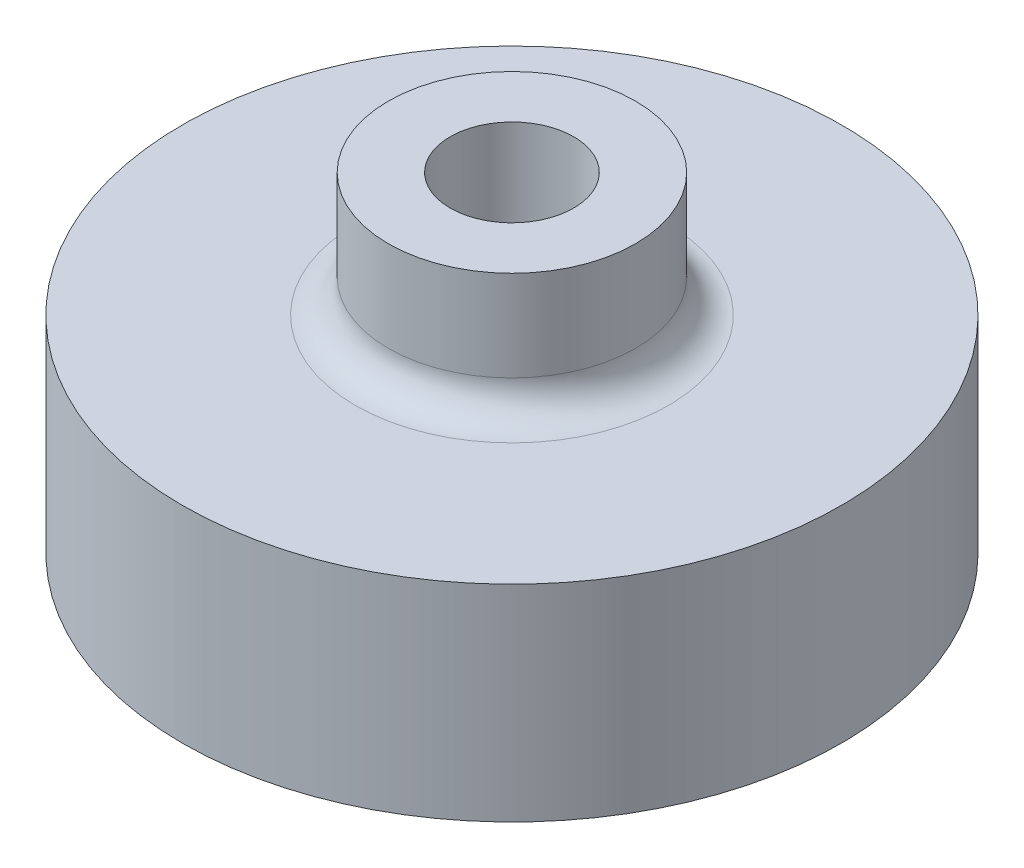
SolidWorks part; units mm, degrees
ref_plane "Front Plane" through (0, 0, 0) normal (0, 0, 1) x (1, 0, 0)
ref_plane "Top Plane" through (0, 0, 0) normal (0, 1, 0) x (1, 0, 0)
ref_plane "Right Plane" through (0, 0, 0) normal (1, 0, 0) x (0, 0, -1)
sketch "Sketch1" plane through (0, 0, 0) normal (0, 1, 0) x (1, 0, 0)
  circle A0 centre (0, 0) radius 1000
extrude "Boss-Extrude1" add sketch "Sketch1" along normal blind 625
sketch "Sketch2" plane through (0, 625, 0) normal (0, 1, 0) x (1, 0, 0)
  circle A0 centre (0, 0) radius 375
extrude "Boss-Extrude2" add sketch "Sketch2" along normal blind 375
fillet "Fillet1" radius 100 1 edges at (0, 625, 375)
sketch "Sketch3" plane through (0, 1000, 0) normal (0, 1, 0) x (1, 0, 0)
  circle A0 centre (0, 0) radius 187.5
extrude "Cut-Extrude1" cut sketch "Sketch3" against normal blind 875
sketch "Sketch4" plane through (0, 0, 0) normal (0, -1, 0) x (-1, 0, 0)
  line L2 (-48.0876, -187.5) -> (-48.0876, 181.2287)
  line L3 (50, -187.5) -> (50, 180.7104)
  arc A0 (50, -180.7104) -> (50, 180.7104) centre (0, 0) ccw
  arc A1 (-48.0876, 181.2287) -> (-48.0876, -181.2287) centre (0, 0) ccw
extrude "Cut-Extrude2" cut sketch "Sketch4" against normal blind 125 contours L3 A0 | L2 A1
